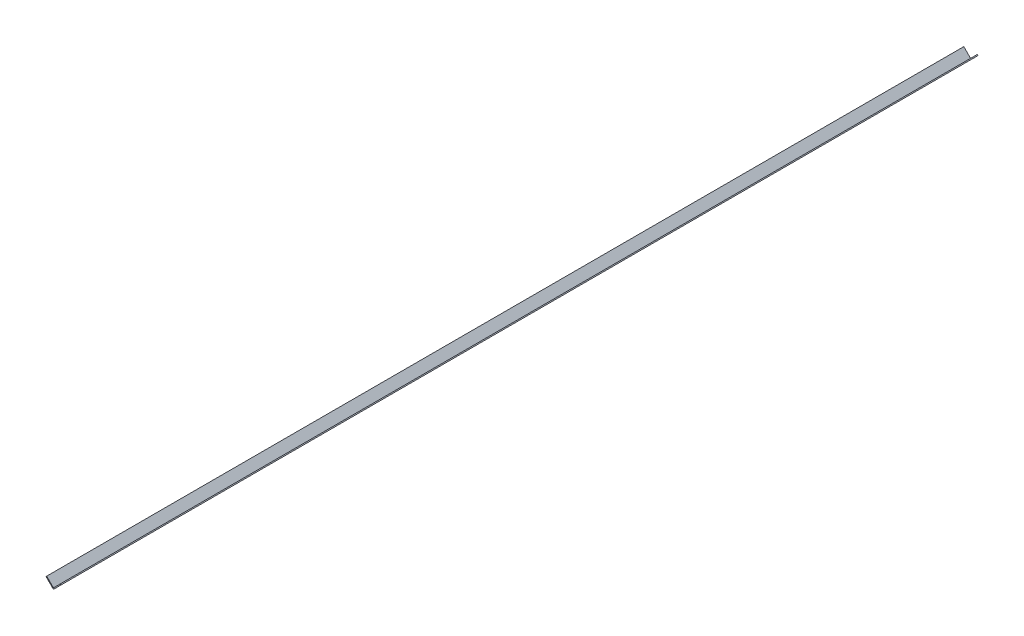
SolidWorks part; units mm, degrees
material "6061 Alloy"
ref_plane "Front Plane" through (0, 0, 0) normal (0, 0, 1) x (1, 0, 0)
ref_plane "Top Plane" through (0, 0, 0) normal (0, 1, 0) x (1, 0, 0)
ref_plane "Right Plane" through (0, 0, 0) normal (1, 0, 0) x (0, 0, -1)
sketch "Sketch1" plane through (0, 0, 0) normal (0, 0, 1) x (1, 0, 0)
  line L0 (0, 0) -> (-8.9803, 8.9803)
  line L1 (-8.9803, 8.9803) -> (-9.8783, 8.0822)
  line L2 (-9.8783, 8.0822) -> (0, -1.7961)
  line L3 (0, -1.7961) -> (9.8783, 8.0822)
  line L4 (9.8783, 8.0822) -> (8.9803, 8.9803)
  line L5 (8.9803, 8.9803) -> (0, 0)
  line L6 (-13.872, 0) -> (16.6117, 0) construction
  dimension "D1" = 1.27
  dimension "D2" = 12.7
extrude "Boss-Extrude1" add sketch "Sketch1" along normal blind 1143 and the other way blind 76.2
